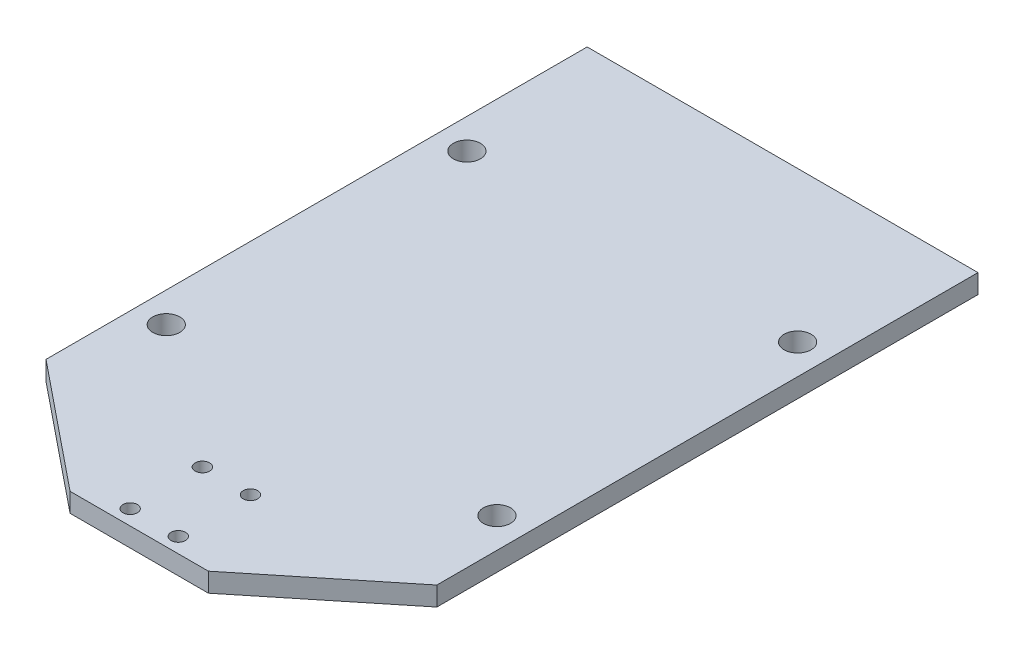
SolidWorks part; units mm, degrees
material "6061-T6 (SS)"
ref_plane "Front Plane" through (0, 0, 0) normal (0, 0, 1) x (1, 0, 0)
ref_plane "Top Plane" through (0, 0, 0) normal (0, 1, 0) x (1, 0, 0)
ref_plane "Right Plane" through (0, 0, 0) normal (1, 0, 0) x (0, 0, -1)
sketch "Sketch1" plane through (0, 0, 0) normal (0, 1, 0) x (1, 0, 0)
  line L0 (-11.5, -62) -> (-32.5, -45)
  line L1 (32.5, -45) -> (-32.5, -45)
  line L2 (32.5, -45) -> (32.5, 45)
  line L3 (32.5, 45) -> (-32.5, 45)
  line L4 (-32.5, -45) -> (-32.5, 45)
  line L5 (32.5, -45) -> (-32.5, 45) construction
  line L6 (32.5, 45) -> (-32.5, -45) construction
  line L7 (-11.5, -45) -> (11.5, -45)
  line L8 (-11.5, -45) -> (-11.5, -62)
  line L9 (-11.5, -62) -> (11.5, -62)
  line L10 (11.5, -45) -> (11.5, -62)
  line L11 (11.5, -62) -> (32.5, -45)
  line L12 (-32.5, -45) -> (32.5, -45)
  line L13 (11.5, -62) -> (-11.5, -62)
  point P0 (0, 0)
  point P10 (0, -62)
  dimension "D1" = 90
  dimension "D2" = 65
  dimension "D3" = 23
  dimension "D4" = 17
  dimension "D5" = 32.5
extrude "Boss-Extrude1" add sketch "Sketch1" along normal mid plane 3.175 contours L8 L1 L0 | L10 L11 L1 | L4 L1 L2 L3 | L10 L1 L8 L9
sketch "Sketch4" plane through (0, 1.5875, 0) normal (0, 1, 0) x (1, 0, 0)
  line L0 (-11.5, -62) -> (11.5, -62) construction
  point P0 (-4, -59.5)
  point P2 (4, -59.5)
  point P4 (4, -47.5)
  point P6 (-4, -47.5)
  point P16 (0, -62)
  dimension "D1" = 8
  dimension "D2" = 12
  dimension "D3" = 4
  dimension "D4" = 2.5
hole_wizard "M2 Clearance Hole1" positions "Sketch4" profile "Sketch3" hole size "M2" standard "ANSI Metric" end condition through all
sketch "Sketch3" plane through (-4, 1.5875, 59.5) normal (1, 0, 0) x (0, 0, 1)
  line L0 (0, 0) -> (0, 3.175)
  line L1 (0, 3.175) -> (1.2, 3.175)
  line L2 (1.2, 3.175) -> (1.2, 0)
  line L5 (1.2, 0) -> (0, 0)
  line L11 (0, -6.35) -> (0, 107.95) construction
  dimension "Thru Hole Dia." = 2.4
  dimension "Thru Hole Depth" = 3.175
sketch "Sketch7" plane through (0, 1.5875, 0) normal (0, 1, 0) x (1, 0, 0)
  line L0 (-32.5, -45) -> (-32.5, 45) construction
  line L1 (32.5, -45) -> (32.5, 45) construction
  line L2 (32.5, 45) -> (-32.5, 45) construction
  point P0 (-27.5, 20)
  point P2 (27.5, 20)
  point P4 (27.5, -30)
  point P6 (-27.5, -30)
  dimension "D1" = 5
  dimension "D2" = 5
  dimension "D3" = 25
  dimension "D4" = 50
hole_wizard "M4 Clearance Hole1" positions "Sketch7" profile "Sketch6" hole size "M4" standard "ANSI Metric" end condition through all
sketch "Sketch6" plane through (-27.5, 1.5875, -20) normal (1, 0, 0) x (0, 0, 1)
  line L0 (0, 0) -> (0, 3.175)
  line L1 (0, 3.175) -> (2.25, 3.175)
  line L2 (2.25, 3.175) -> (2.25, 0)
  line L5 (2.25, 0) -> (0, 0)
  line L11 (0, -6.35) -> (0, 107.95) construction
  dimension "Thru Hole Dia." = 4.5
  dimension "Thru Hole Depth" = 3.175
